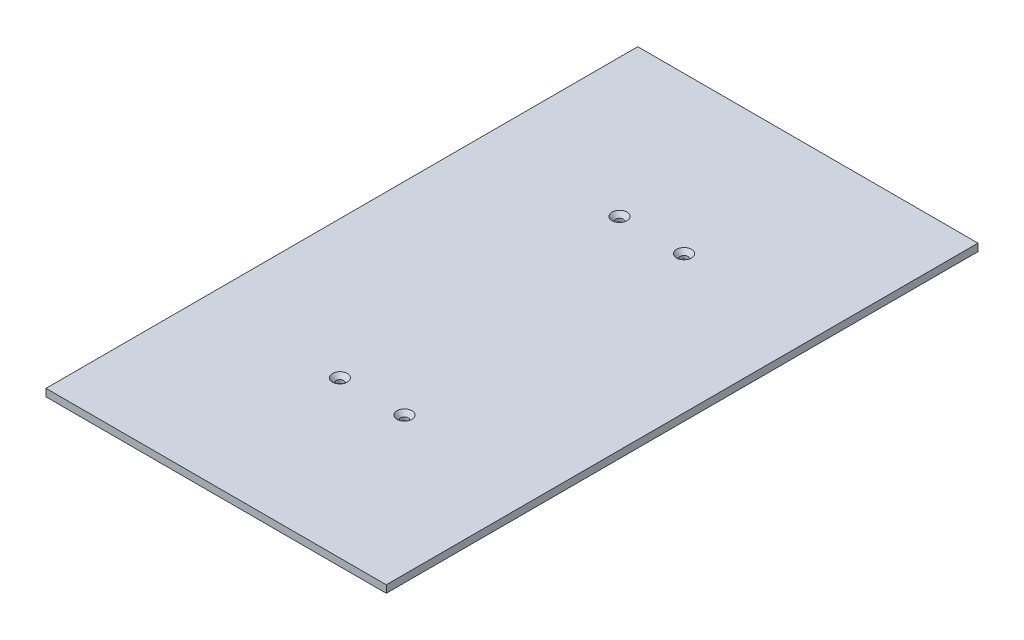
SolidWorks part; units mm, degrees
ref_plane "Front Plane" through (0, 0, 0) normal (0, 0, 1) x (1, 0, 0)
ref_plane "Top Plane" through (0, 0, 0) normal (0, 1, 0) x (1, 0, 0)
ref_plane "Right Plane" through (0, 0, 0) normal (1, 0, 0) x (0, 0, -1)
sketch "Sketch1" plane through (0, 0, 0) normal (0, 1, 0) x (1, 0, 0)
  line L0 (0.9272, 231.0049) -> (293.0272, 231.0049) construction
  line L1 (0.9272, -22.9951) -> (293.0272, -22.9951)
  line L2 (0.9272, -22.9951) -> (0.9272, 485.0049)
  line L3 (0.9272, 485.0049) -> (293.0272, 485.0049)
  line L4 (293.0272, -22.9951) -> (293.0272, 485.0049)
  line L5 (293.0272, 231.0049) -> (146.9772, 485.0049) construction
  line L6 (146.9772, 485.0049) -> (0.9272, 231.0049) construction
  dimension "D1" = 508
  dimension "D2" = 292.1
extrude "Boss-Extrude1" add sketch "Sketch1" along normal blind 6.35 contours L2 L3 L4 L1
sketch "Sketch5" plane through (0, 6.35, 0) normal (0, 1, 0) x (1, 0, 0)
  line L5 (0.9272, 485.0049) -> (293.0272, 485.0049)
  line L6 (0.9272, 485.0049) -> (0.9272, -22.9951)
  line L7 (0.9272, -22.9951) -> (293.0272, -22.9951)
  line L8 (293.0272, 485.0049) -> (293.0272, -22.9951)
  line L9 (146.9772, -22.9951) -> (146.9772, 485.0049) construction
  line L10 (0.9272, 231.0049) -> (293.0272, 231.0049) construction
  circle A0 centre (174.6772, 351.0049) radius 3.5
  circle A1 centre (119.2772, 351.0049) radius 3.5
  circle A2 centre (174.6772, 111.0049) radius 3.5
  circle A3 centre (119.2772, 111.0049) radius 3.5
  point P168 (146.9772, 231.0049)
  dimension "D1" = 7
  dimension "D3" = 120
  dimension "D2" = 27.7
hole_wizard "CSK for 1/4 Flat Head Machine Screw1" positions "3DSketch1" profile "Sketch6" countersink size "1/4" standard "ANSI Inch" end condition through all
sketch3d "3DSketch1"
  point P0 (119.2772, 6.35, -351.0049)
  point P3 (174.6772, 6.35, -351.0049)
  point P6 (174.6772, 6.35, -111.0049)
  point P9 (119.2772, 6.35, -111.0049)
sketch "Sketch6" plane through (119.2772, 6.35, -351.0049) normal (1, 0, 0) x (0, 0, 1)
  line L0 (0, 0) -> (0, 6.35)
  line L1 (0, 6.35) -> (3.2639, 6.35)
  line L2 (3.2639, 6.35) -> (3.2639, 3.6524)
  line L3 (3.2639, 3.6524) -> (6.4389, 0)
  line L5 (6.4389, 0) -> (0, 0)
  line L6 (-3.2639, 3.6524) -> (-6.4389, 0) construction
  line L11 (0, -6.35) -> (0, 107.95) construction
  dimension "Thru Hole Dia." = 6.5278
  dimension "Thru Hole Depth" = 6.35
  dimension "Near C'Sink Dia." = 12.8778
  dimension "Near C'Sink Angle" = 82
